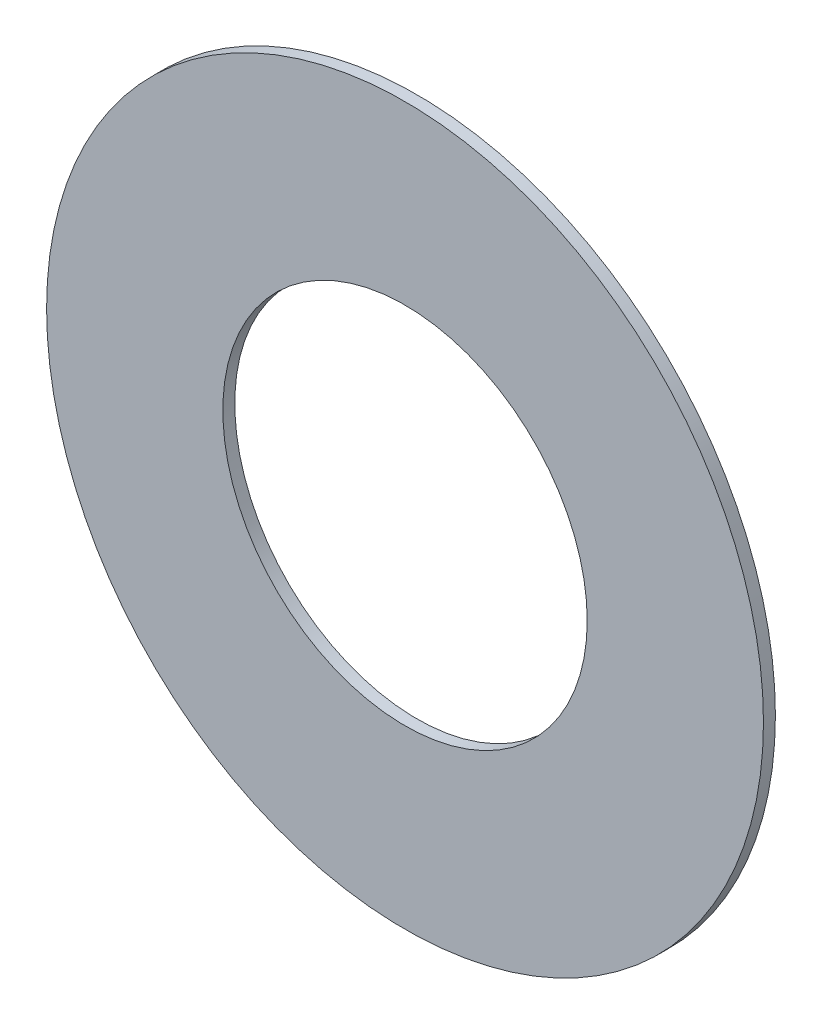
SolidWorks part; units mm, degrees
material "1.8159 (51CrV4)"
ref_plane "Front Plane" through (0, 0, 0) normal (0, 0, 1) x (1, 0, 0)
ref_plane "Top Plane" through (0, 0, 0) normal (0, 1, 0) x (1, 0, 0)
ref_plane "Right Plane" through (0, 0, 0) normal (1, 0, 0) x (0, 0, -1)
sketch "Sketch1" plane through (0, 0, 0) normal (0, 0, 1) x (1, 0, 0)
  circle A0 centre (0, 0) radius 12
  circle A1 centre (0, 0) radius 6.1
extrude "Boss-Extrude1" add sketch "Sketch1" along normal blind 0.4
